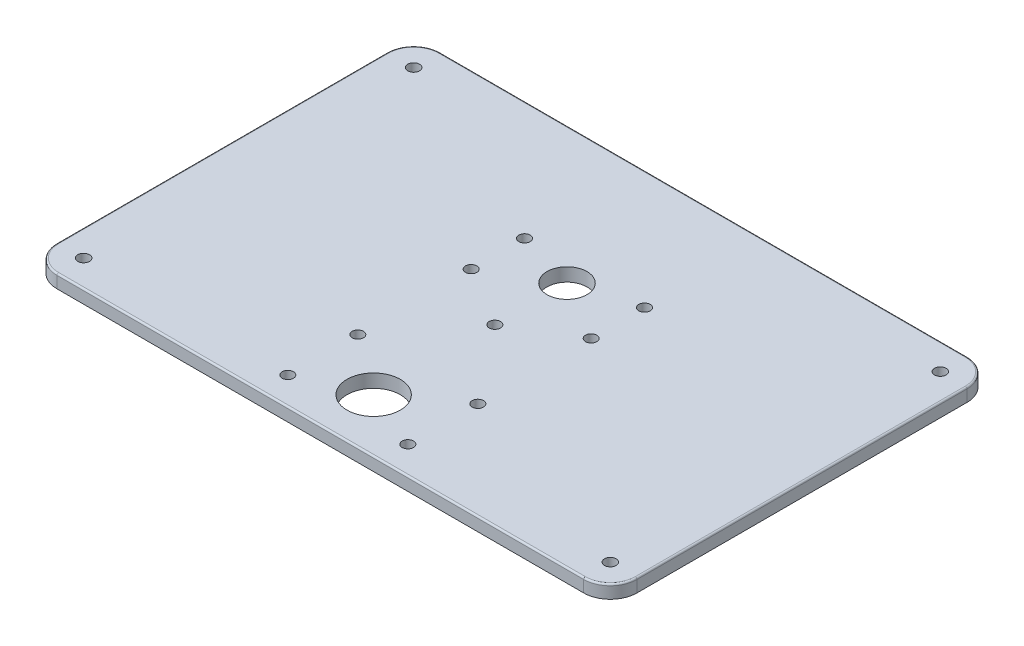
SolidWorks part; units mm, degrees
material "ABS"
ref_plane "Front Plane" through (0, 0, 0) normal (0, 0, 1) x (1, 0, 0)
ref_plane "Top Plane" through (0, 0, 0) normal (0, 1, 0) x (1, 0, 0)
ref_plane "Right Plane" through (0, 0, 0) normal (1, 0, 0) x (0, 0, -1)
sketch "Reference" plane through (0, 0, 0) normal (0, 1, 0) x (1, 0, 0)
  line L0 (-79, -96) -> (79, -96) construction
  line L1 (87, -88) -> (87, 88) construction
  line L2 (79, 96) -> (-79, 96) construction
  line L3 (-87, 88) -> (-87, -88) construction
  circle A0 centre (0, -3) radius 16.25 construction
  arc A1 (-79, -96) -> (-87, -88) centre (-79, -88) cw construction
  arc A2 (79, -96) -> (87, -88) centre (79, -88) ccw construction
  arc A3 (87, 88) -> (79, 96) centre (79, 88) ccw construction
  arc A4 (-79, 96) -> (-87, 88) centre (-79, 88) ccw construction
  circle A5 centre (-65, 78) radius 1.75 construction
  circle A6 centre (65, 78) radius 1.75 construction
  circle A7 centre (65, -78) radius 1.75 construction
  circle A8 centre (-65, -78) radius 1.75 construction
  point P6 (0, -96)
  dimension "D1" = 32.5
  dimension "D3" = 8
  dimension "D4" = 3.5
  dimension "D2" = 93
  dimension "D5" = 130
  dimension "D6" = 22
  dimension "D7" = 22
  dimension "D8" = 156
  dimension "D9" = 18
  dimension "D10" = 18
sketch "Sketch2" plane through (0, 0, 0) normal (0, 1, 0) x (1, 0, 0)
  line L0 (87, -88) -> (87, 88) construction
  line L1 (-87, 88) -> (-87, -88) construction
  line L3 (87, -11) -> (87, 88)
  line L4 (-87, 88) -> (-87, -11)
  line L6 (-79, -19) -> (79, -19)
  line L13 (79, 96) -> (-79, 96)
  arc A0 (87, -11) -> (79, -19) centre (79, -11) cw
  arc A1 (87, 88) -> (79, 96) centre (79, 88) ccw construction
  arc A2 (-79, 96) -> (-87, 88) centre (-79, 88) ccw construction
  arc A4 (87, 88) -> (79, 96) centre (79, 88) ccw
  arc A5 (-79, 96) -> (-87, 88) centre (-79, 88) ccw
  arc A6 (-87, -11) -> (-79, -19) centre (-79, -11) ccw
  circle A26 centre (-79, 88) radius 1.75
  circle A27 centre (79, 88) radius 1.75
  circle A28 centre (79, -11) radius 1.75
  circle A29 centre (-79, -11) radius 1.75
  circle A30 centre (-65, 78) radius 1.75 construction
  circle A35 centre (0, -3) radius 8
  circle A36 centre (18, -10.75) radius 1.7
  circle A37 centre (18, 10.25) radius 1.7
  circle A38 centre (-18, -10.75) radius 1.7
  circle A49 centre (-18, 10.25) radius 1.7
  circle A54 centre (0, 33.35) radius 1.7
  circle A55 centre (18, 60.25) radius 1.7
  circle A56 centre (18, 44.25) radius 1.7
  circle A57 centre (-18, 44.25) radius 1.7
  circle A58 centre (0, 55) radius 6
  circle A59 centre (-18, 60.25) radius 1.7
  point P0 (0, -3)
  point P11 (0, 0)
  point P15 (0, 0)
  point P18 (0, 0)
  point P19 (0, 0)
  point P20 (78.1427, -19)
  point P21 (0, 0)
  point P22 (78.1427, 96)
  point P28 (0, 0)
  point P45 (0, 0)
  point P46 (0, 0)
  point P47 (0, 0)
  point P48 (0, 0)
  point P49 (0, 0)
  point P50 (0, 0)
  point P51 (0, 0)
  point P52 (0, 0)
  point P53 (0, 0)
  point P54 (0, 0)
  point P55 (1.4777, 34.2866)
  point P56 (0, 0)
  dimension "D2" = 8
  dimension "D3" = 58
  dimension "D6" = 16
  dimension "D10" = 10.75
  dimension "D7" = 18
  dimension "D5" = 12
  dimension "D4" = 52.35
  dimension "D8" = 18
  dimension "D9" = 5.25
  dimension "D11" = 13.25
  dimension "D12" = 115
  dimension "D13" = 8
  dimension "D14" = 8
  dimension "D15" = 99
  dimension "D16" = 7.75
extrude "Boss-Extrude1" add sketch "Sketch2" along normal blind 4
fillet "Fillet1" radius 0.5 8 edges at (-84.6569, 4, 16.6569) (-87, 4, -38.5) (-84.6569, 4, -93.6569) (0, 4, -96) (84.6569, 4, -93.6569) (87, 4, -38.5) (84.6569, 4, 16.6569) (0, 4, 19)
